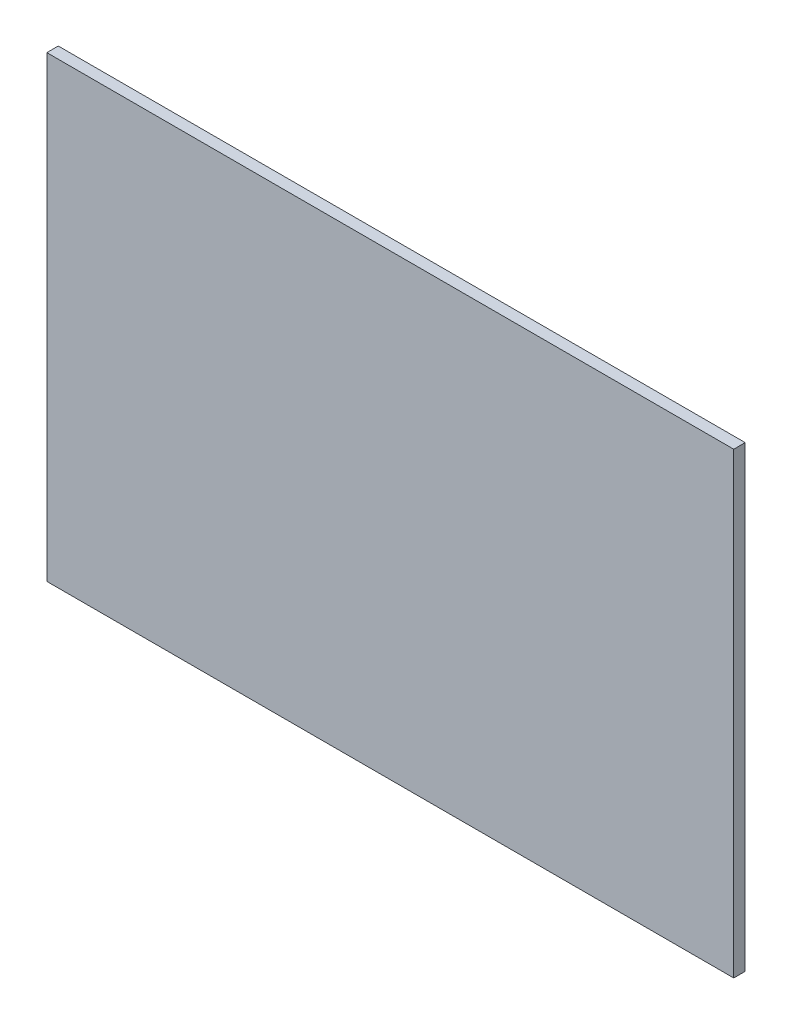
SolidWorks part; units mm, degrees
ref_plane "Front Plane" through (0, 0, 0) normal (0, 0, 1) x (1, 0, 0)
ref_plane "Top Plane" through (0, 0, 0) normal (0, 1, 0) x (1, 0, 0)
ref_plane "Right Plane" through (0, 0, 0) normal (1, 0, 0) x (0, 0, -1)
sketch "草图1" plane through (0, 0, 0) normal (0, 0, 1) x (1, 0, 0)
  line L1 (0, 0) -> (600, 0)
  line L2 (0, 0) -> (0, 400)
  line L3 (0, 400) -> (600, 400)
  line L4 (600, 0) -> (600, 400)
  dimension "D1" = 600
  dimension "D2" = 400
extrude "凸台-拉伸1" add sketch "草图1" along normal blind 10 contours L2 L3 L4 L1
